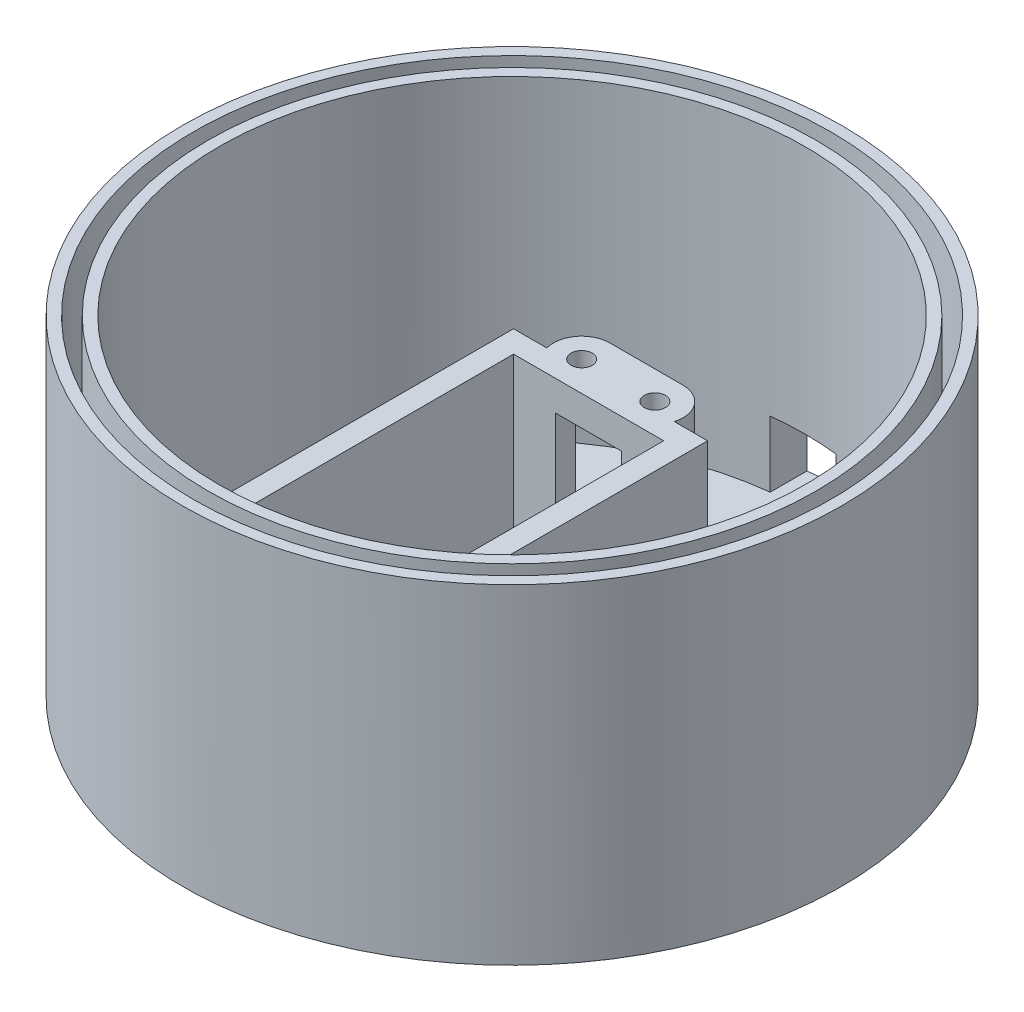
SolidWorks part; units mm, degrees
ref_plane "Alzado" through (0, 0, 0) normal (0, 0, 1) x (1, 0, 0)
ref_plane "Planta" through (0, 0, 0) normal (0, 1, 0) x (1, 0, 0)
ref_plane "Vista lateral" through (0, 0, 0) normal (1, 0, 0) x (0, 0, -1)
sketch "Croquis2" plane through (0, 0, 0) normal (0, 1, 0) x (1, 0, 0)
  line L0 (-10.8387, 0) -> (0, 0) construction
  line L1 (0, 5) -> (0, -5) construction
  line L2 (-23.45, 5) -> (-23.45, -5)
  line L3 (-13.25, -23.45) -> (13.25, -23.45)
  line L4 (-13.25, -23.45) -> (-13.25, -8.45)
  line L5 (-13.25, 23.45) -> (13.25, 23.45)
  line L6 (13.25, -23.45) -> (13.25, -8.45)
  line L7 (-13.25, -23.45) -> (13.25, 23.45) construction
  line L8 (-13.25, 23.45) -> (13.25, -23.45) construction
  line L9 (-20, -8.45) -> (-13.25, -8.45)
  line L10 (20, -8.45) -> (13.25, -8.45)
  line L11 (23.45, -5) -> (23.45, 5)
  line L12 (20, 8.45) -> (13.25, 8.45)
  line L13 (-20, 8.45) -> (-13.25, 8.45)
  line L14 (-13.25, 8.45) -> (-13.25, 23.45)
  line L15 (13.25, 8.45) -> (13.25, 23.45)
  circle A0 centre (-20, 5) radius 1.45
  circle A1 centre (-20, -5) radius 1.45
  circle A2 centre (20, -5) radius 1.45
  circle A3 centre (20, 5) radius 1.45
  arc A4 (-20, 8.45) -> (-23.45, 5) centre (-20, 5) ccw
  arc A5 (-20, -8.45) -> (-23.45, -5) centre (-20, -5) cw
  arc A6 (20, 8.45) -> (23.45, 5) centre (20, 5) cw
  arc A7 (20, -8.45) -> (23.45, -5) centre (20, -5) ccw
  circle A8 centre (-20, 0) radius 1.45
  circle A9 centre (-20, 5) radius 3.45 construction
  circle A10 centre (-20, -5) radius 3.45 construction
  circle A11 centre (20, 5) radius 3.45 construction
  circle A12 centre (20, -5) radius 3.45 construction
  circle A13 centre (20, 0) radius 1.45
  point P18 (-16.55, -5)
  point P20 (23.45, 5)
  point P22 (23.45, -5)
  point P37 (-16.55, 5)
  dimension "D1" = 2.9
  dimension "D2" = 5
  dimension "D3" = 20
  dimension "D7" = 2.9
  dimension "D8" = 20
  dimension "D4" = 26.5
  dimension "D5" = 46.9
  dimension "D6" = 2
extrude "Saliente-Extruir1" add sketch "Croquis2" along normal blind 2
sketch "Croquis3" plane through (0, 2, 0) normal (0, 1, 0) x (1, 0, 0)
  line L0 (-10.25, 20.45) -> (-10.25, -20.45)
  line L1 (-13.25, 23.45) -> (13.25, 23.45)
  line L2 (-13.25, 23.45) -> (-13.25, -23.45)
  line L3 (-13.25, -23.45) -> (13.25, -23.45)
  line L4 (13.25, 23.45) -> (13.25, -23.45)
  line L5 (-10.25, -20.45) -> (10.25, -20.45)
  line L6 (10.25, 20.45) -> (10.25, -20.45)
  line L7 (-10.25, 20.45) -> (10.25, 20.45)
  dimension "D1" = 3
extrude "Saliente-Extruir2" add sketch "Croquis3" along normal blind 28.1
sketch "Croquis4" plane through (0, 30.1, 0) normal (0, 1, 0) x (1, 0, 0)
  line L0 (0, 0) -> (0, 28.3845) construction
  line L1 (0, 0) -> (26.4868, 0) construction
  line L2 (-5, 28.3482) -> (5, 28.3482)
  line L4 (-8.7022, -23.45) -> (8.7022, -23.45)
  line L11 (-8.7022, 23.45) -> (8.7022, 23.45)
  line L12 (13.25, 23.45) -> (-13.25, 23.45) construction
  line L13 (-5, -28.3482) -> (5, -28.3482)
  circle A0 centre (-5, 24.5) radius 1.8482 construction
  arc A1 (-5, 28.3482) -> (-8.7022, 23.45) centre (-5, 24.5) ccw
  arc A2 (5, 28.3482) -> (8.7022, 23.45) centre (5, 24.5) cw
  circle A4 centre (-5, 24.5) radius 3.8482 construction
  arc A6 (-5, -28.3482) -> (-8.7022, -23.45) centre (-5, -24.5) cw
  arc A7 (5, -28.3482) -> (8.7022, -23.45) centre (5, -24.5) ccw
  point P18 (0.9482, 22.5)
  dimension "D1" = 5
  dimension "D2" = 24.5
  dimension "D3" = 2
extrude "Saliente-Extruir3" add sketch "Croquis4" against normal blind 3.5
sketch "Croquis5" plane through (0, 30.1, 0) normal (0, 1, 0) x (1, 0, 0)
  line L0 (0, 0) -> (26.4424, 0) construction
  line L1 (0, 0) -> (0, 31.0192) construction
  circle A0 centre (-5, 24.5) radius 1.45
  circle A1 centre (5, 24.5) radius 1.45
  circle A2 centre (5, -24.5) radius 1.45
  circle A3 centre (-5, -24.5) radius 1.45
  dimension "D1" = 2.9
extrude "Cortar-Extruir1" cut sketch "Croquis5" against normal through all
sketch "Croquis6" plane through (0, 0, -23.45) normal (0, 0, -1) x (-1, 0, 0)
  line L0 (-13.25, 2) -> (13.25, 2) construction
  line L1 (0, 0) -> (0, 36.2929) construction
  line L2 (-4.5, 2) -> (4.5, 2)
  line L3 (-4.5, 2) -> (-4.5, 26)
  line L4 (-4.5, 26) -> (4.5, 26)
  line L5 (4.5, 2) -> (4.5, 26)
  dimension "D1" = 9
  dimension "D2" = 4.5
  dimension "D3" = 24
extrude "Cortar-Extruir2" cut sketch "Croquis6" against normal blind 3.5
sketch "Croquis7" plane through (0, 0, 0) normal (0, -1, 0) x (1, 0, 0)
  line L0 (0, 0) -> (-38.6016, 0) construction
  line L1 (0, 0) -> (0, -36.8674) construction
  line L2 (5, -28.3482) -> (-5, -28.3482) construction
  circle A0 centre (0, -9.9982) radius 45
  dimension "D1" = 18.35
  dimension "D2" = 90
extrude "Saliente-Extruir4" add sketch "Croquis7" against normal blind 2
sketch "Croquis8" plane through (0, 2, 0) normal (0, 1, 0) x (1, 0, 0)
  circle A0 centre (0, 9.9982) radius 45
  circle A1 centre (0, 9.9982) radius 40
  circle A2 centre (0, 9.9982) radius 45 construction
  dimension "D2" = 0
  dimension "D1" = 5
extrude "Saliente-Extruir5" add sketch "Croquis8" along normal blind 43
sketch "Croquis9" plane through (0, 45, 0) normal (0, 1, 0) x (1, 0, 0)
  circle A0 centre (0, 9.9982) radius 41.5
  circle A1 centre (0, 9.9982) radius 43.5
  circle A2 centre (0, 9.9982) radius 45 construction
  dimension "D1" = 2
  dimension "D2" = 1.5
extrude "Cortar-Extruir3" cut sketch "Croquis9" against normal blind 30
sketch "Croquis10" plane through (0, 0, -23.45) normal (0, 0, -1) x (-1, 0, 0)
  line L0 (0, 0) -> (0, 48.5002) construction
  line L1 (-45, 0) -> (45, 0) construction
  line L2 (-4.5, 2) -> (4.5, 2)
  line L3 (-4.5, 2) -> (-4.5, 11)
  line L4 (-4.5, 11) -> (4.5, 11)
  line L5 (4.5, 2) -> (4.5, 11)
  line L6 (-4.5, 2) -> (4.5, 11) construction
  line L7 (-4.5, 11) -> (4.5, 2) construction
  point P3 (0, 6.5)
  dimension "D1" = 2
  dimension "D2" = 9
  dimension "D3" = 9
extrude "Cortar-Extruir4" cut sketch "Croquis10" along normal through all
sketch "Croquis11" plane through (0, 2, 0) normal (0, 1, 0) x (1, 0, 0)
  line L0 (0, 54.9982) -> (0, -35.0018) construction
  line L1 (-45, 9.9982) -> (45, 9.9982) construction
  circle A0 centre (0, 9.9982) radius 45 construction
  circle A1 centre (-20, 9.9982) radius 1.45
  circle A2 centre (20, 9.9982) radius 1.45
  dimension "D1" = 20
  dimension "D2" = 2.9
extrude "Cortar-Extruir5" cut sketch "Croquis11" against normal through all
